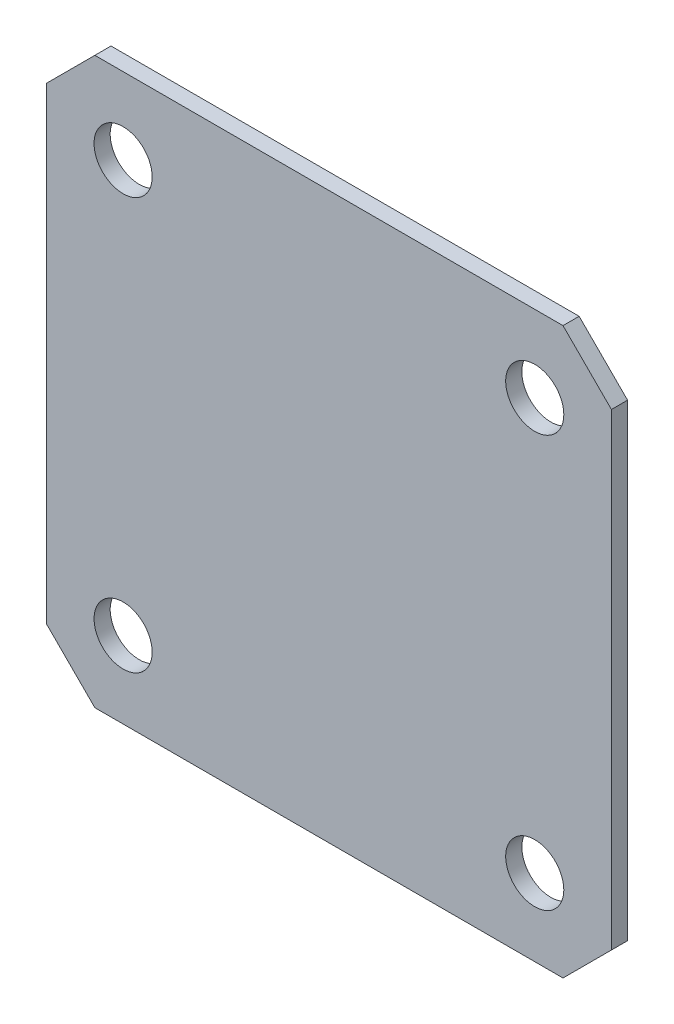
SolidWorks part; units mm, degrees
ref_plane "Front Plane" through (0, 0, 0) normal (0, 0, 1) x (1, 0, 0)
ref_plane "Top Plane" through (0, 0, 0) normal (0, 1, 0) x (1, 0, 0)
ref_plane "Right Plane" through (0, 0, 0) normal (1, 0, 0) x (0, 0, -1)
sketch "Sketch1" plane through (0, 0, 0) normal (0, 0, 1) x (1, 0, 0)
  line L1 (-17.5, 17.5) -> (17.5, 17.5)
  line L2 (-17.5, 17.5) -> (-17.5, -17.5)
  line L3 (-17.5, -17.5) -> (17.5, -17.5)
  line L4 (17.5, 17.5) -> (17.5, -17.5)
  line L5 (-12.75, 12.75) -> (12.75, 12.75) construction
  line L6 (-12.75, 12.75) -> (-12.75, -12.75) construction
  line L7 (-12.75, -12.75) -> (12.75, -12.75) construction
  line L8 (12.75, 12.75) -> (12.75, -12.75) construction
  circle A0 centre (-12.75, 12.75) radius 1.8
  circle A1 centre (12.75, 12.75) radius 1.8
  circle A2 centre (-12.75, -12.75) radius 1.8
  circle A3 centre (12.75, -12.75) radius 1.8
  point P4 (0, 17.5)
  point P5 (-17.5, 0)
  point P11 (0, 12.75)
  point P12 (-12.75, 0)
  dimension "D2" = 3.6
  dimension "D1" = 35
  dimension "D3" = 25.5
extrude "Extrude1" add sketch "Sketch1" along normal blind 1
chamfer "Chamfer1" distance 3 angle 45 4 edges at (-17.5, 17.5, 0.5) (17.5, 17.5, 0.5) (17.5, -17.5, 0.5) (-17.5, -17.5, 0.5)
